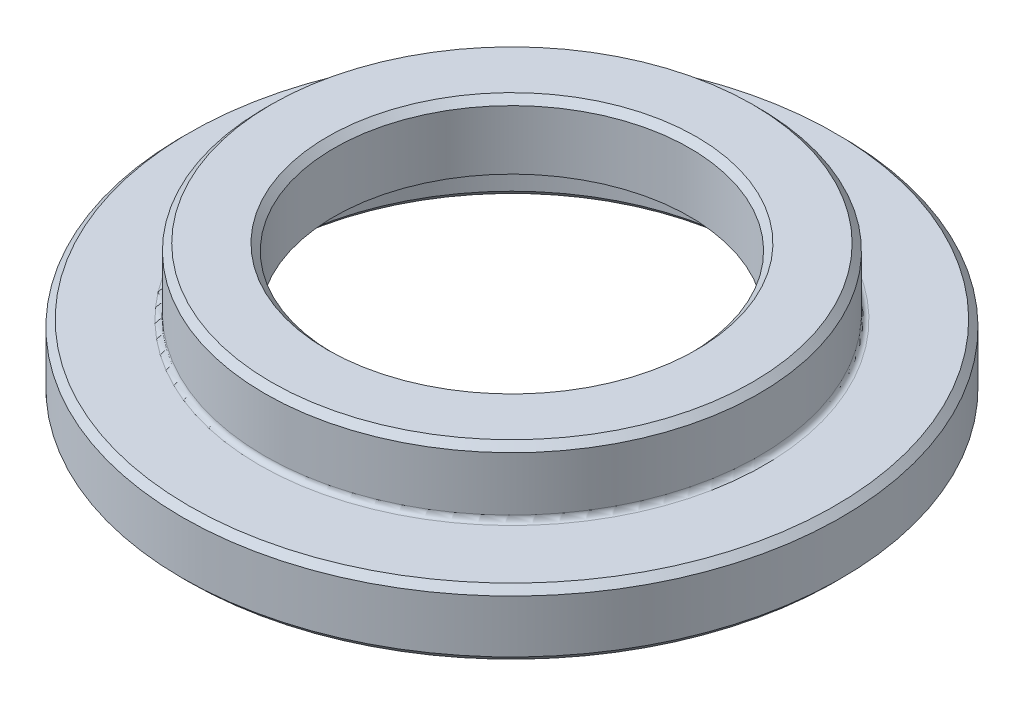
SolidWorks part; units mm, degrees
ref_plane "Front Plane" through (0, 0, 0) normal (0, 0, 1) x (1, 0, 0)
ref_plane "Top Plane" through (0, 0, 0) normal (0, 1, 0) x (1, 0, 0)
ref_plane "Right Plane" through (0, 0, 0) normal (1, 0, 0) x (0, 0, -1)
sketch "Sketch2" plane through (0, 0, 0) normal (0, 1, 0) x (1, 0, 0)
  circle A0 centre (0, 0) radius 12.7
  circle A1 centre (0, 0) radius 9.2837
  dimension "D1" = 25.4
  dimension "D2" = 18.5674
extrude "Boss-Extrude1" add sketch "Sketch2" along normal blind 2.54 contours A0 A1
sketch "Sketch3" plane through (0, 2.54, 0) normal (0, 1, 0) x (1, 0, 0)
  circle A0 centre (0, 0) radius 9.2837 construction
  circle A1 centre (0, 0) radius 12.7
  circle A2 centre (0, 0) radius 12.7
  circle A3 centre (0, 0) radius 9.2837
  circle A4 centre (0, 0) radius 9.525
  circle A5 centre (0, 0) radius 6.858
  dimension "D2" = 19.05
  dimension "D3" = 13.716
  dimension "D1" = 0
extrude "Boss-Extrude2" add sketch "Sketch3" along normal blind 2.54 contours A5 | A4
fillet "Fillet1" radius 0.2032 2 edges at (0, 2.54, 9.2837) (0, 2.54, 9.525)
chamfer "Chamfer1" distance 0.254 angle 45 5 edges at (0, 0, 12.7) (0, 0, 9.2837) (0, 5.08, 6.858) (0, 5.08, 9.525) (0, 2.54, 12.7)
